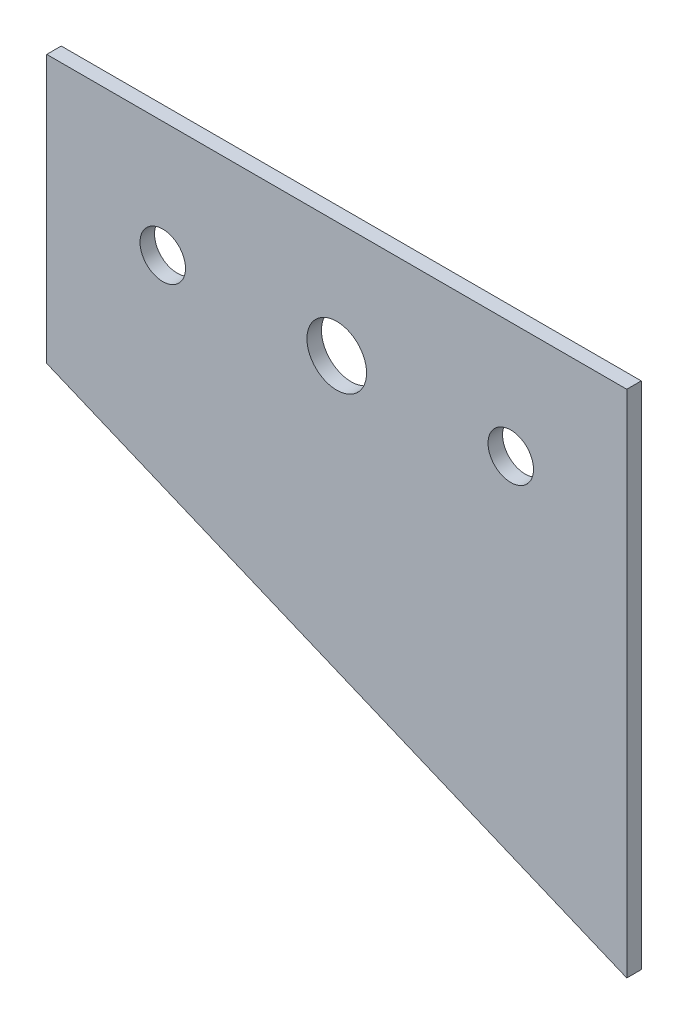
SolidWorks part; units mm, degrees
material "AISI 1010 Steel, hot rolled bar"
ref_plane "Front Plane" through (0, 0, 0) normal (0, 0, 1) x (1, 0, 0)
ref_plane "Top Plane" through (0, 0, 0) normal (0, 1, 0) x (1, 0, 0)
ref_plane "Right Plane" through (0, 0, 0) normal (1, 0, 0) x (0, 0, -1)
sketch "Sketch1" plane through (0, 0, 0) normal (0, 0, 1) x (1, 0, 0)
  line L2 (1461.2304, -334.6113) -> (1461.2304, -278.7912)
  line L4 (1461.2304, -278.7912) -> (1397.7304, -278.7912)
  line L5 (1397.7304, -278.7912) -> (1397.7304, -308.0952)
  line L7 (1397.7304, -308.0952) -> (1461.2304, -334.6113)
  circle A0 centre (1410.4304, -291.493) radius 2.4892
  circle A1 centre (1448.5304, -291.493) radius 2.4892
  circle A2 centre (1429.4804, -291.493) radius 3.2639
  point P8 (1429.4804, -278.7912)
  dimension "D3" = 12.7018
  dimension "D5" = 4.9784
  dimension "D6" = 6.5278
  dimension "D1" = 29.304
  dimension "D2" = 63.5
  dimension "D4" = 112.664
  dimension "D8" = 12.7
  dimension "D9" = 12.7
extrude "Boss-Extrude1" add sketch "Sketch1" along normal blind 1.5875
sketch "Sketch2" plane through (0, 0, 1.5875) normal (0, 0, 1) x (1, 0, 0)
  circle A0 centre (1429.4804, -291.493) radius 3.2639 construction
  circle A1 centre (1429.4804, -291.493) radius 3.2639
